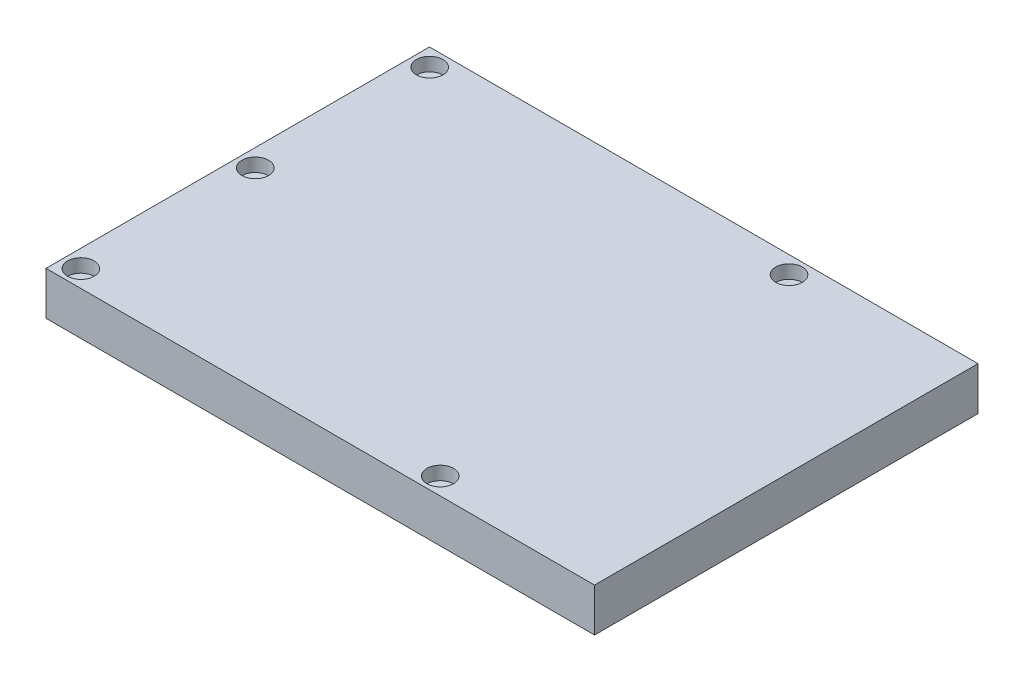
SolidWorks part; units mm, degrees
ref_plane "Front Plane" through (0, 0, 0) normal (0, 0, 1) x (1, 0, 0)
ref_plane "Top Plane" through (0, 0, 0) normal (0, 1, 0) x (1, 0, 0)
ref_plane "Right Plane" through (0, 0, 0) normal (1, 0, 0) x (0, 0, -1)
sketch "Sketch1" plane through (0, 0, 0) normal (0, 1, 0) x (1, 0, 0)
  line L8 (-63.3366, 44.2745) -> (-63.3366, -44.2745)
  line L9 (-63.3366, -44.2745) -> (63.3366, -44.2745)
  line L10 (63.3366, -44.2745) -> (63.3366, 44.2745)
  line L11 (63.3366, 44.2745) -> (-63.3366, 44.2745)
  point P6 (0, 0)
extrude "Boss-Extrude1" add sketch "Sketch1" along normal blind 10
sketch "Sketch2" plane through (0, 10, 0) normal (0, 1, 0) x (1, 0, 0)
  line L0 (-63.2653, 44.2495) -> (-55.264, 36.2487) construction
  line L1 (23.7198, 36.2487) -> (23.7198, 44.2495) construction
  line L2 (23.7198, 40.2491) -> (-63.2653, 40.2491) construction
  line L3 (-55.264, -0.025) -> (-63.2653, -0.025) construction
  line L4 (-55.264, -36.2986) -> (-63.2653, -44.2995) construction
  line L5 (23.7198, -36.2986) -> (23.7198, -44.2995) construction
  line L6 (-59.2646, -40.2991) -> (63.1737, -40.2991) construction
  line L7 (23.7198, 40.2491) -> (63.4078, 40.2491) construction
  circle A0 centre (-59.2646, 40.2491) radius 3.075
  circle A1 centre (-59.2646, -0.025) radius 3.075
  circle A2 centre (-59.2646, -40.2991) radius 3.075
  circle A3 centre (23.7198, -40.2991) radius 3.075
  circle A4 centre (23.7198, 40.2491) radius 3.075
  point P23 (0, 0)
  point P24 (0, 0)
extrude "Cut-Extrude1" cut sketch "Sketch2" against normal blind 3.1
